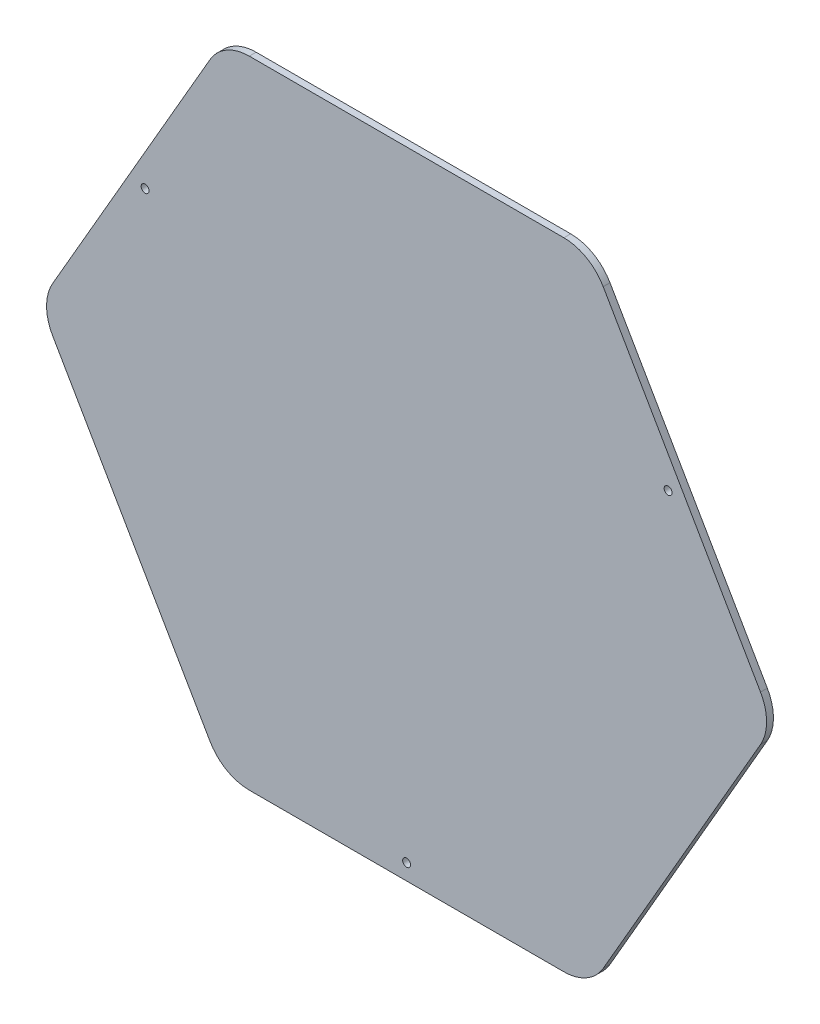
SolidWorks part; units mm, degrees
ref_plane "Alzado" through (0, 0, 0) normal (0, 0, 1) x (1, 0, 0)
ref_plane "Planta" through (0, 0, 0) normal (0, 1, 0) x (1, 0, 0)
ref_plane "Vista lateral" through (0, 0, 0) normal (1, 0, 0) x (0, 0, -1)
sketch "Croquis1" plane through (0, 0, 0) normal (0, 0, 1) x (1, 0, 0)
  line L0 (11.25, 96) -> (-11.25, 84) construction
  line L1 (-11.25, 96) -> (11.25, 96)
  line L2 (-11.25, 96) -> (-11.25, 84)
  line L3 (-11.25, 84) -> (11.25, 84)
  line L4 (11.25, 96) -> (11.25, 84)
  line L5 (-11.25, 96) -> (11.25, 84) construction
  line L6 (88.7634, -38.2572) -> (78.3711, -32.2572)
  line L7 (88.7634, -38.2572) -> (77.5134, -57.7428)
  line L8 (77.5134, -57.7428) -> (67.1211, -51.7428)
  line L9 (78.3711, -32.2572) -> (67.1211, -51.7428)
  line L10 (-77.5134, -57.7428) -> (-67.1211, -51.7428)
  line L11 (-77.5134, -57.7428) -> (-88.7634, -38.2572)
  line L12 (-88.7634, -38.2572) -> (-78.3711, -32.2572)
  line L13 (-67.1211, -51.7428) -> (-78.3711, -32.2572)
  line L14 (0, -0.7536) -> (0, 0) construction
  line L15 (0, 0) -> (0, 17.5) construction
  line L17 (-80.829, -140) -> (80.829, -140)
  line L18 (80.829, -140) -> (161.6581, 0)
  line L19 (161.6581, 0) -> (80.829, 140)
  line L20 (80.829, 140) -> (-80.829, 140)
  line L21 (-80.829, 140) -> (-161.6581, 0)
  line L22 (-161.6581, 0) -> (-80.829, -140)
  circle A0 centre (0, 0) radius 150
  circle A1 centre (0, 0) radius 10.8
  circle A2 centre (0, 0) radius 90 construction
  circle A3 centre (0, 90) radius 40 construction
  circle A4 centre (77.9423, -45) radius 40 construction
  circle A5 centre (-77.9423, -45) radius 40 construction
  circle A6 centre (0, 0) radius 17.5 construction
  circle A7 centre (0, 17.5) radius 2.6
  circle A8 centre (0, 0) radius 140 construction
  circle A9 centre (15.1554, -8.75) radius 2.6
  circle A10 centre (-15.1554, -8.75) radius 2.6
  point P11 (0, 90)
  point P18 (0, 0)
  point P28 (0, 0)
  point P39 (0, 0)
  dimension "D1" = 300
  dimension "D2" = 21.6
  dimension "D3" = 180
  dimension "D4" = 80
  dimension "D9" = 5.2
  dimension "D10" = 3
  dimension "D11" = 50
  dimension "D5" = 12
  dimension "D6" = 22.5
  dimension "D7" = 3
  dimension "D8" = 3
extrude "Saliente-Extruir1" add sketch "Croquis1" along normal blind 3 contours L19 A0 L20 L21 L22 L17 L18 A10 A9 A7 A1 L1 L4 L3 L2 L9 L6 L7 L8 L13 L10 L11 L12 | A0 L20 L21 | A0 L19 L20 | A0 L18 L19 | A0 L17 L18 | A0 L22 L17 | A0 L21 L22 | A10 | A1 | A9 | A7
fillet "Redondeo1" radius 20 6 edges at (80.829, 140, 1.5) (-80.829, 140, 1.5) (-161.6581, 0, 1.5) (-80.829, -140, 1.5) (80.829, -140, 1.5) (161.6581, 0, 1.5)
sketch "Croquis2" plane through (0, 0, 0) normal (0, 0, -1) x (1, 0, 0)
  circle A0 centre (0, 133) radius 1.75
  circle A1 centre (115.1814, -66.5) radius 1.75
  circle A2 centre (-115.1814, -66.5) radius 1.75
  point P9 (0, 0)
  dimension "D1" = 3
extrude "Cortar-Extruir1" cut sketch "Croquis2" against normal through all
